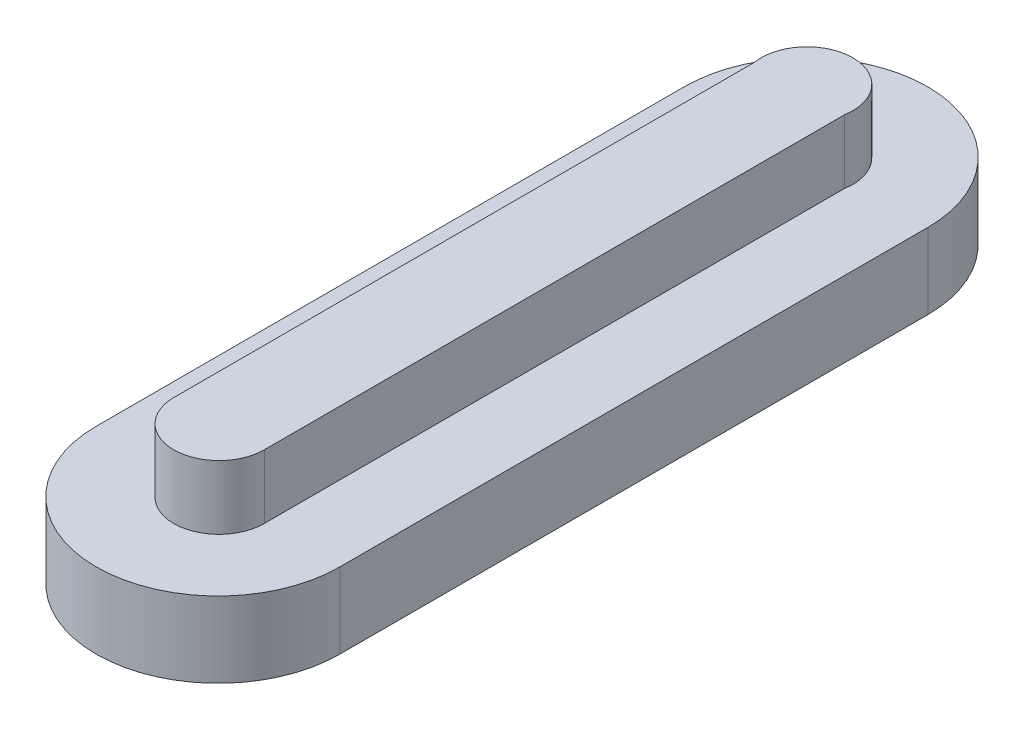
SolidWorks part; units mm, degrees
ref_plane "Front" through (0, 0, 0) normal (0, 0, 1) x (1, 0, 0)
ref_plane "Top" through (0, 0, 0) normal (0, 1, 0) x (1, 0, 0)
ref_plane "Right" through (0, 0, 0) normal (1, 0, 0) x (0, 0, -1)
sketch "Sketch1" plane through (0, 0, 0) normal (0, 1, 0) x (1, 0, 0)
  line L0 (0, 0) -> (0, -35) construction
  line L1 (7.25, 0) -> (7.25, -35)
  line L2 (-7.25, 0) -> (-7.25, -35)
  arc A0 (7.25, 0) -> (-7.25, 0) centre (0, 0) ccw
  arc A1 (-7.25, -35) -> (7.25, -35) centre (0, -35) ccw
  point P3 (0, -17.5)
extrude "Boss-Extrude1" add sketch "Sketch1" along normal blind 4.5
sketch "Sketch3" plane through (0, 4.5, 0) normal (0, 1, 0) x (1, 0, 0)
  line L1 (-2.6226, -0.0113) -> (2.7638, -0.0113)
  line L2 (-2.6226, -0.0113) -> (-2.6226, -35.0113)
  line L3 (-2.6226, -35.0113) -> (2.7638, -35.0113)
  line L4 (2.7638, -0.0113) -> (2.7638, -35.0113)
  circle A0 centre (0.0706, -0.0113) radius 2.7299
  circle A1 centre (0.0706, -35.0113) radius 2.6932
  dimension "D1" = 35
extrude "Boss-Extrude2" add sketch "Sketch3" along normal blind 3.8 contours L4 A0 L2 L1 | A1 L4 A0 L2 | L3 A1 | L3 A1 | L2 A0 L4 L1
sketch "Sketch4" plane through (0, 8.3, 0) normal (0, 1, 0) x (1, 0, 0)
  line L0 (0, 0) -> (0.0706, -35.0113) construction
  line L1 (7.2531, 0.0146) -> (7.3237, -34.9967)
  line L2 (-7.2531, -0.0146) -> (-7.1825, -35.0259)
  arc A0 (7.2531, 0.0146) -> (-7.2531, -0.0146) centre (0, 0) ccw
  arc A1 (-7.1825, -35.0259) -> (7.3237, -34.9967) centre (0.0706, -35.0113) ccw
  point P4 (0.0353, -17.5056)
extrude "Boss-Extrude3" add sketch "Sketch4" along normal blind 8.1
sketch "Sketch6" plane through (0, 16.4, 0) normal (0, 1, 0) x (1, 0, 0)
  line L1 (4.4439, 25.9416) -> (-24.5798, 25.9416)
  line L2 (4.4439, 25.9416) -> (4.4439, -52.1157)
  line L3 (4.4439, -52.1157) -> (-24.5798, -52.1157)
  line L4 (-24.5798, 25.9416) -> (-24.5798, -52.1157)
  line L5 (-24.5798, 36.4587) -> (23.3831, 36.4587)
  line L6 (-24.5798, 36.4587) -> (-24.5798, -65.8474)
  line L7 (-24.5798, -65.8474) -> (23.3831, -65.8474)
  line L8 (23.3831, 36.4587) -> (23.3831, -65.8474)
  arc M5 (7.2531, 0.0146) -> (-7.2531, -0.0146) centre (0, 0) ccw
  line M6 (-7.2531, -0.0146) -> (-7.1825, -35.0259)
  arc M7 (-7.1825, -35.0259) -> (7.3237, -34.9967) centre (0.0706, -35.0113) ccw
  line M8 (7.3237, -34.9967) -> (7.2531, 0.0146)
extrude "Cut-Extrude2" cut sketch "Sketch6" against normal blind 8.1 contours L8 L5 L6 L1 L2 L3 L7 M5 M8 M7 | L1 L4 L3 L2 M7 M6 M5 | L2 M5 M6 M7 | L2 M5 M7 M8
